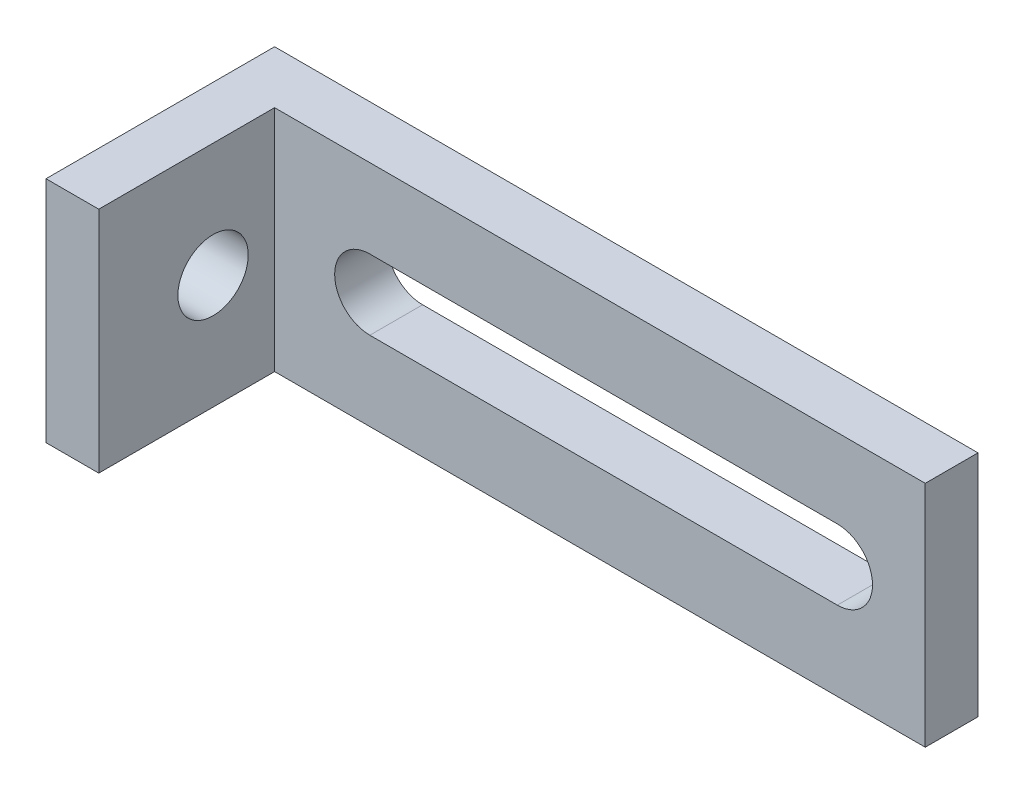
SolidWorks part; units mm, degrees
ref_plane "Front Plane" through (0, 0, 0) normal (0, 0, 1) x (1, 0, 0)
ref_plane "Top Plane" through (0, 0, 0) normal (0, 1, 0) x (1, 0, 0)
ref_plane "Right Plane" through (0, 0, 0) normal (1, 0, 0) x (0, 0, -1)
sketch "Sketch2" plane through (0, 0, 0) normal (0, 0, 1) x (1, 0, 0)
  line L1 (-20, 6.5) -> (20, 6.5)
  line L2 (-20, 6.5) -> (-20, -6.5)
  line L3 (-20, -6.5) -> (20, -6.5)
  line L4 (20, 6.5) -> (20, -6.5)
  line L5 (-20, 6.5) -> (20, -6.5) construction
  line L6 (-20, -6.5) -> (20, 6.5) construction
  point P0 (0, 0)
  dimension "D1" = 13
  dimension "D2" = 40
extrude "Boss-Extrude1" add sketch "Sketch2" along normal blind 3
sketch "Sketch3" plane through (0, 0, 3) normal (0, 0, 1) x (1, 0, 0)
  line L0 (-20, -6.5) -> (20, -6.5) construction
  line L1 (-20, 6.5) -> (-17, 6.5)
  line L2 (-20, 6.5) -> (-20, -6.5)
  line L3 (-20, -6.5) -> (-17, -6.5)
  line L4 (-17, 6.5) -> (-17, -6.5)
  dimension "D1" = 3
extrude "Boss-Extrude2" add sketch "Sketch3" along normal blind 10
sketch "Sketch4" plane through (-20, 0, 0) normal (-1, 0, 0) x (0, 0, 1)
  line L0 (13, 6.5) -> (0, 6.5) construction
  line L1 (13, 6.5) -> (13, -6.5) construction
  circle A0 centre (6.5, 0) radius 2
  dimension "D1" = 4
  dimension "D2" = 6.5
  dimension "D3" = 6.5
extrude "Cut-Extrude1" cut sketch "Sketch4" against normal blind 12
sketch "Sketch5" plane through (0, 0, 0) normal (0, 0, -1) x (-1, 0, 0)
  line L0 (-15, 0) -> (11.5846, 0) construction
  line L1 (-15, 2) -> (11.5846, 2)
  line L2 (-15, -2) -> (11.5846, -2)
  line L3 (-20, 6.5) -> (20, 6.5) construction
  line L4 (-20, -6.5) -> (-20, 6.5) construction
  arc A0 (-15, 2) -> (-15, -2) centre (-15, 0) ccw
  arc A1 (11.5846, -2) -> (11.5846, 2) centre (11.5846, 0) ccw
  point P2 (-1.7077, 0)
  dimension "D1" = 2
  dimension "D3" = 5
  dimension "D2" = 6.5
extrude "Cut-Extrude2" cut sketch "Sketch5" against normal blind 12
